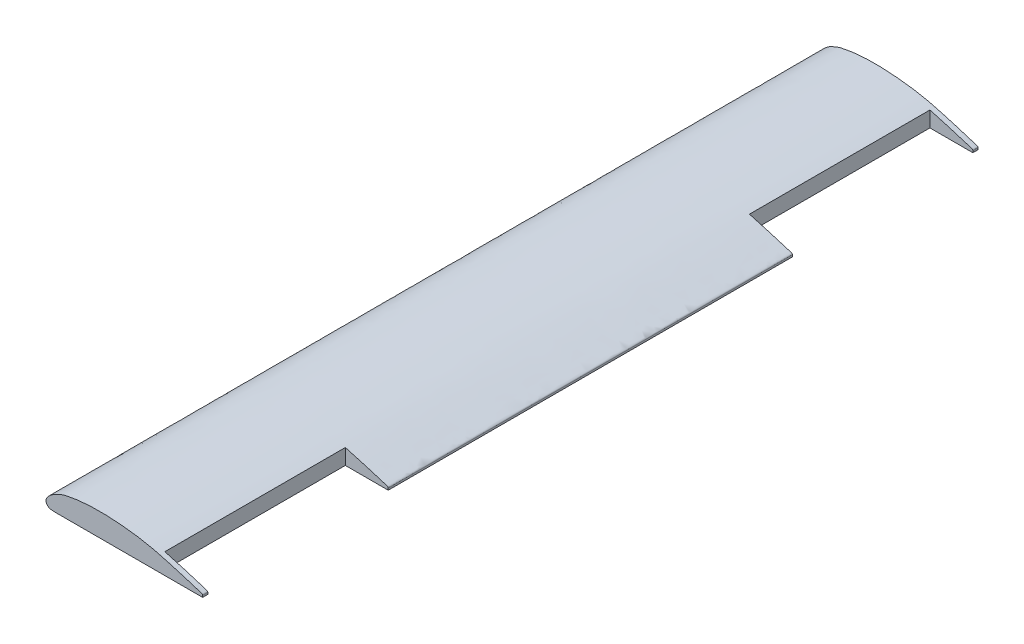
SolidWorks part; units mm, degrees
material "Massless Nylon"
ref_plane "Front" through (0, 0, 0) normal (0, 0, 1) x (1, 0, 0)
ref_plane "Top" through (0, 0, 0) normal (0, 1, 0) x (1, 0, 0)
ref_plane "Right" through (0, 0, 0) normal (1, 0, 0) x (0, 0, -1)
sketch "Sketch1" plane through (0, 0, 0) normal (0, 0, 1) x (1, 0, 0)
  line L4 (306.2919, 0.0613) -> (306.2919, 1.9292)
  line L5 (19.7805, 0.0613) -> (306.2919, 0.0613)
  spline S2 degree 3 poles (306.2919, 1.9292) (306.5644, 2.6011) (288.6662, 7.516) (272.0897, 13.0674) (244.8457, 20.9506) (215.0827, 29.45) (184.3445, 35.6859) (153.7843, 39.4102) (123.2577, 41.727) (92.7189, 42.0509) (67.2581, 40.2024) (46.9897, 36.9966) (34.1193, 34.2502) (24.1598, 30.0231) (16.3672, 26.232) (10.0131, 21.6905) (4.0782, 16.1734) (-0.3651, 8.5499) (4.4871, 2.0301) (10.4333, 0.3691) (15.3034, 0.0978) (18.8184, 0.0605) (19.7805, 0.0613) knots 0 0 0 0 0.025556 0.05096 0.101553 0.151805 0.201252 0.250083 0.298629 0.347026 0.395536 0.420003 0.444885 0.457915 0.471441 0.486208 0.494594 0.510948 0.521395 0.527824 0.539982 0.544566 0.544566 0.544566 0.544566
extrude "Boss-Extrude1" add sketch "Sketch1" along normal blind 1524 contours S2 L5 L4
sketch "Thara'sAileron" plane through (0, 0, 1524) normal (0, 0, 1) x (1, 0, 0)
  spline S0 degree 3 poles (202.8847, -71.0414) (229.0683, -74.2156) (202.697, -66.7637) (186.1531, -61.0868) (158.9536, -52.9979) (129.2382, -44.2739) (98.5306, -37.8072) (67.9823, -33.8548) (37.4573, -31.3109) (6.9053, -30.7608) (-18.5822, -32.4218) (-38.8847, -35.4792) (-51.782, -38.1317) (-61.7779, -42.2873) (-69.6025, -46.0226) (-75.9934, -50.5194) (-81.9722, -55.9953) (-86.4742, -63.5899) (-81.6677, -70.1489) (-75.7308, -71.8548) (-69.2809, -72.262) (-61.6461, -72.2447) (-51.494, -71.6957) (-38.7693, -71.6285) (-18.4913, -69.8254) (6.9169, -68.6889) (37.4056, -68.1516) (67.8987, -68.0047) (98.3401, -68.2147) (128.9695, -68.4361) (158.9205, -69.1698) (185.9768, -71.1133) (202.8847, -71.0414) (229.0683, -74.2156) (202.697, -66.7637) knots -0.096906 -0.048454 -0.024239 0 0.025556 0.05096 0.101553 0.151805 0.201252 0.250083 0.298629 0.347026 0.395536 0.420003 0.444885 0.457915 0.471441 0.486208 0.494594 0.510948 0.521395 0.527824 0.539982 0.55208 0.564187 0.588394 0.612649 0.661101 0.709502 0.757894 0.806286 0.85468 0.903094 0.951546 0.975761 1 1.025556 1.05096 1.101553 only from (220.2903, -72.4838) to (220.2903, -72.4838)
sketch3d "3DSketch1"
  line L0 (306.2919, 1.9292, 1524) -> (306.2919, 1.9292, 0) construction
  line L1 (427.1566, 0, 365.76) -> (221.7319, 0, 365.76)
  line L2 (427.1566, 0, 365.76) -> (427.1566, 0, 6.35)
  line L3 (427.1566, 0, 6.35) -> (221.7319, 0, 6.35)
  line L4 (221.7319, 0, 365.76) -> (221.7319, 0, 6.35)
  line L9 (427.1566, 0, 6.35) -> (306.2919, 1.9292, 0) construction
  point P4 (306.2919, 0, 0)
  dimension "D1" = 359.41
  dimension "D2" = 6.35
  dimension "D5" = 84.582
  dimension "D7" = 121.0468
extrude "Cut-Extrude1" cut sketch "3DSketch1" along direction (0, 1, 0) on the side against the normal through all both and the other way through all
sketch3d "3DSketch3" plane through (0, 0, 0) normal (0, 0, 1) x (1, 0, 0)
  dimension "D1" = 762
ref_plane "Plane1" through (0, 0, 762) normal (0, 0, -1) x (-1, 0, 0)
mirror "Mirror1" about plane through (0, 0, 762) normal (0, 0, -1) of "Cut-Extrude1"
surface "Surface-Offset1" parameters "D1"=1.905
